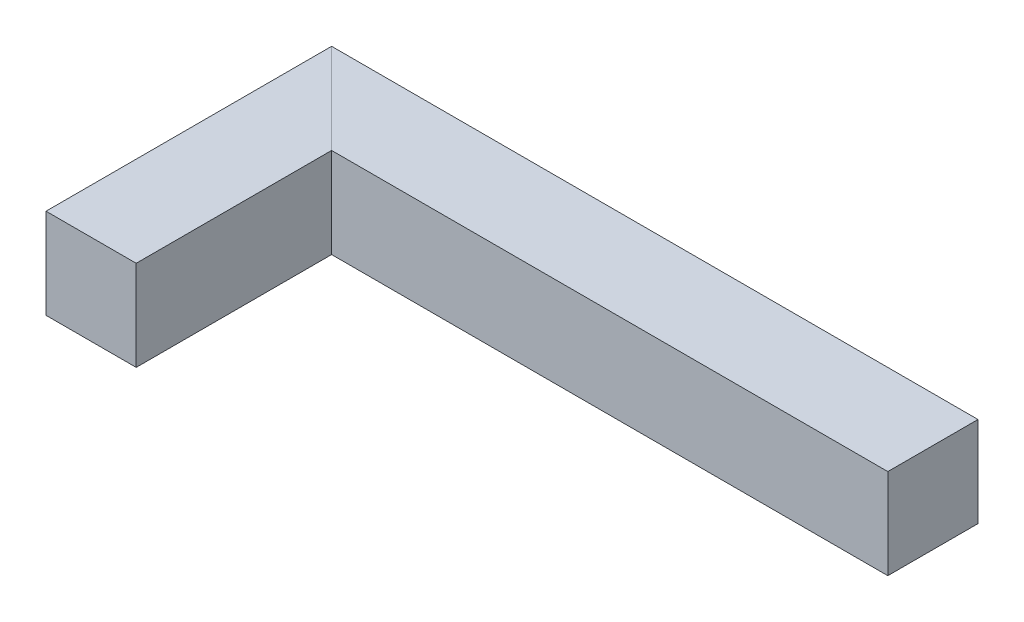
SolidWorks part; units mm, degrees
ref_plane "Front Plane" through (0, 0, 0) normal (0, 0, 1) x (1, 0, 0)
ref_plane "Top Plane" through (0, 0, 0) normal (0, 1, 0) x (1, 0, 0)
ref_plane "Right Plane" through (0, 0, 0) normal (1, 0, 0) x (0, 0, -1)
sketch "Sketch1" plane through (0, 0, 0) normal (0, 0, 1) x (1, 0, 0)
  line L1 (15, -15) -> (-15, -15)
  line L2 (15, -15) -> (15, 15)
  line L3 (15, 15) -> (-15, 15)
  line L4 (-15, -15) -> (-15, 15)
  line L5 (15, -15) -> (-15, 15) construction
  line L6 (15, 15) -> (-15, -15) construction
  point P0 (0, 0)
  dimension "D1" = 30
  dimension "D2" = 30
sketch "Sketch2" plane through (0, 0, 0) normal (0, 1, 0) x (1, 0, 0)
  line L0 (0, 0) -> (0, 80)
  line L1 (0, 80) -> (200, 80)
  dimension "D1" = 80
  dimension "D2" = 200
sweep "Sweep1" add profiles "Sketch1" path "Sketch2"
